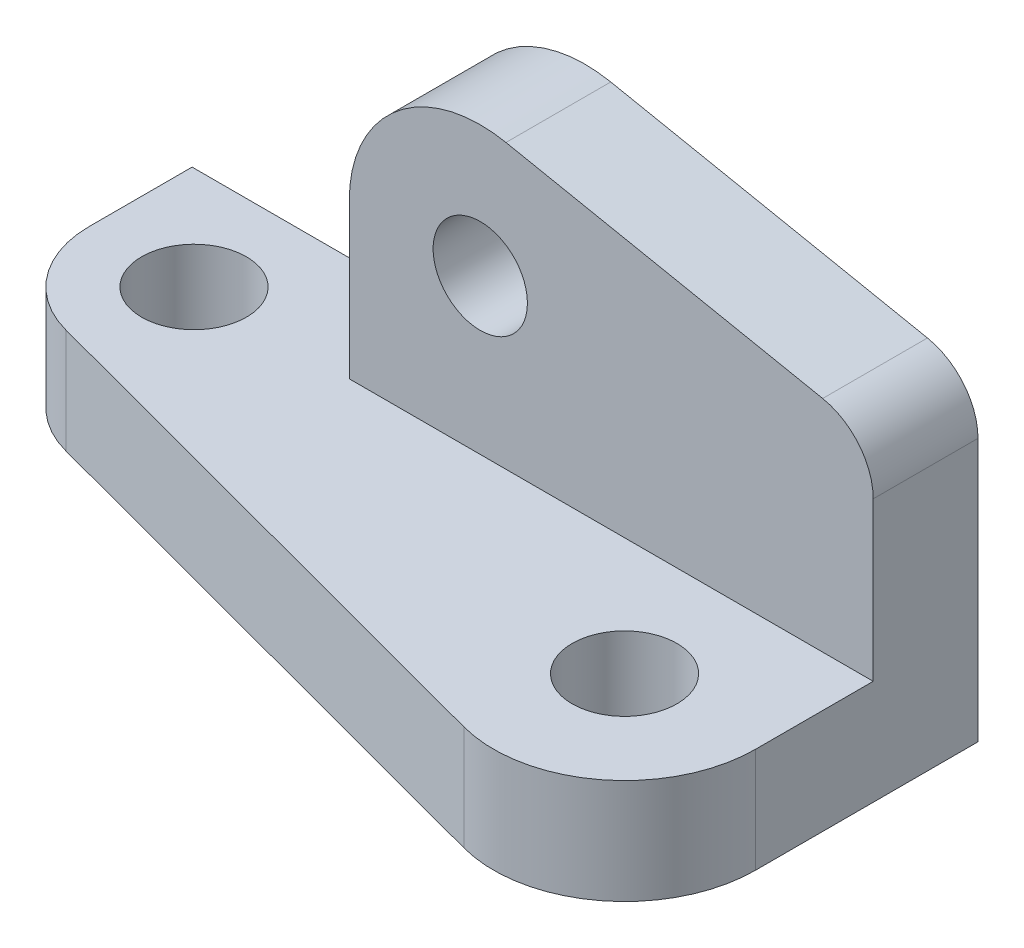
SolidWorks part; units mm, degrees
ref_plane "Front Plane" through (0, 0, 0) normal (0, 0, 1) x (1, 0, 0)
ref_plane "Top Plane" through (0, 0, 0) normal (0, 1, 0) x (1, 0, 0)
ref_plane "Right Plane" through (0, 0, 0) normal (1, 0, 0) x (0, 0, -1)
sketch "Sketch1" plane through (0, 0, 0) normal (0, 1, 0) x (1, 0, 0)
  line L1 (0, 0) -> (150, 0)
  line L2 (0, 0) -> (0, -35)
  line L3 (0, -35) -> (150, -75)
  line L4 (150, 0) -> (150, -75)
  dimension "D1" = 75
  dimension "D2" = 150
  dimension "D3" = 35
extrude "Boss-Extrude1" add sketch "Sketch1" along normal blind 20
sketch "Sketch2" plane through (0, 0, 0) normal (0, 0, -1) x (-1, 0, 0)
  line L1 (-50, 0) -> (-150, 0)
  line L2 (-50, 0) -> (-50, 80)
  line L3 (-50, 80) -> (-150, 60)
  line L4 (-150, 0) -> (-150, 60)
  dimension "D1" = 80
  dimension "D2" = 100
  dimension "D3" = 60
extrude "Boss-Extrude2" add sketch "Sketch2" against normal blind 20
fillet "Fillet1" radius 20 1 edges at (0, 10, 35)
fillet "Fillet2" radius 25 2 edges at (150, 10, 75) (50, 80, 10)
fillet "Fillet3" radius 12 1 edges at (150, 60, 10)
hole_wizard "Ø20.0 (20) Diameter Hole1" positions "Sketch6" profile "Sketch5" hole size "Ø20.0" standard "ANSI Metric" end condition through all
sketch "Sketch6" plane through (0, 20, 0) normal (0, 1, 0) x (1, 0, 0)
  point P0 (20, -19.6344)
  point P3 (125, -42.4597)
sketch "Sketch5" plane through (20, 20, 19.6344) normal (1, 0, 0) x (0, 0, 1)
  line L0 (0, 0) -> (0, 20)
  line L1 (0, 20) -> (10, 20)
  line L2 (10, 20) -> (10, 0)
  line L5 (10, 0) -> (0, 0)
  line L11 (0, -6.35) -> (0, 107.95) construction
  dimension "Thru Hole Dia." = 20
  dimension "Thru Hole Depth" = 20
hole_wizard "Ø18.0 (18) Diameter Hole1" positions "Sketch8" profile "Sketch7" hole size "Ø18.0" standard "ANSI Metric" end condition through all
sketch "Sketch8" plane through (0, 0, 20) normal (0, 0, 1) x (1, 0, 0)
  point P0 (75, 49.5049)
sketch "Sketch7" plane through (75, 49.5049, 20) normal (1, 0, 0) x (0, -1, 0)
  line L0 (0, 0) -> (0, 20)
  line L1 (0, 20) -> (9, 20)
  line L2 (9, 20) -> (9, 0)
  line L5 (9, 0) -> (0, 0)
  line L11 (0, -6.35) -> (0, 107.95) construction
  dimension "Thru Hole Dia." = 18
  dimension "Thru Hole Depth" = 20
